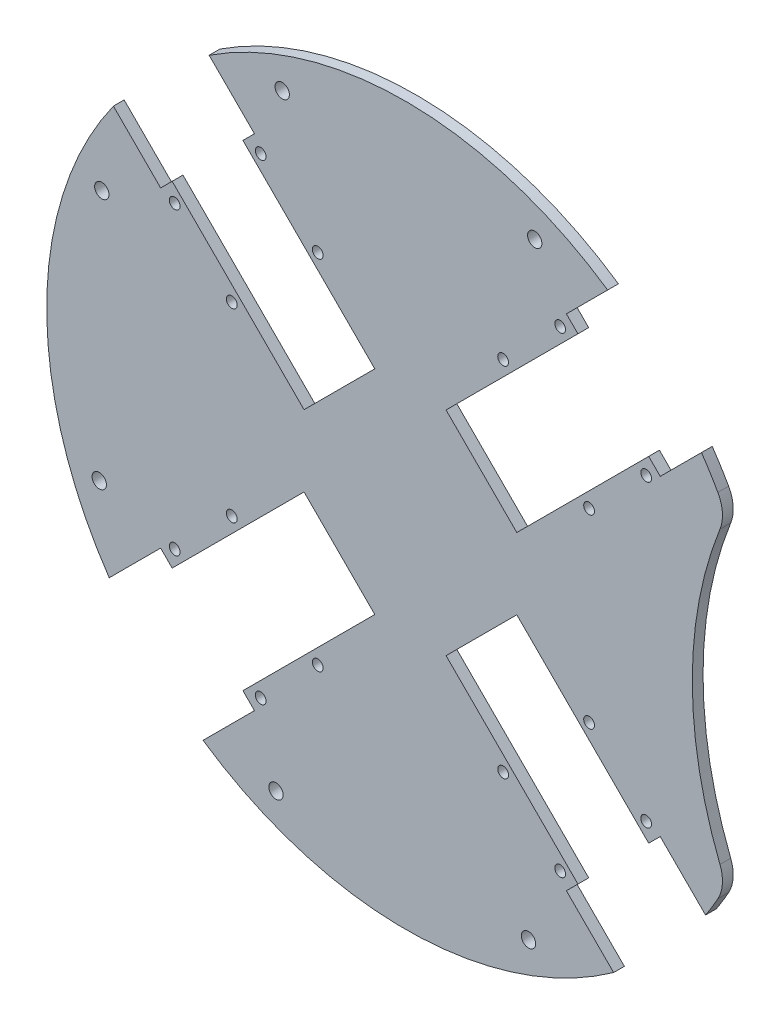
SolidWorks part; units mm, degrees
ref_plane "Alzado" through (0, 0, 0) normal (0, 0, 1) x (1, 0, 0)
ref_plane "Planta" through (0, 0, 0) normal (0, 1, 0) x (1, 0, 0)
ref_plane "Vista lateral" through (0, 0, 0) normal (1, 0, 0) x (0, 0, -1)
sketch "Croquis1" plane through (0, 0, 0) normal (0, 0, 1) x (1, 0, 0)
  circle A0 centre (0, 0) radius 100
  dimension "D1" = 200
extrude "Saliente-Extruir1" add sketch "Croquis1" along normal blind 3
sketch "Croquis3" plane through (0, 0, 3) normal (0, 0, 1) x (1, 0, 0)
  line L0 (0, 0) -> (190, 0) construction
  circle A0 centre (190, 0) radius 110
  dimension "D1" = 220
  dimension "D2" = 190
extrude "Cortar-Extruir1" cut sketch "Croquis3" against normal blind 3
fillet "Redondeo1" radius 10 2 edges at (89.4737, -44.6594, 1.5) (89.4737, 44.6594, 1.5)
sketch "Croquis4" plane through (0, 0, 3) normal (0, 0, 1) x (1, 0, 0)
  line L0 (0, 0) -> (-70.7107, -70.7107) construction
  line L1 (-83.7922, -57.6292) -> (-57.6292, -83.7922)
  line L2 (-57.6292, -83.7922) -> (-42.0729, -68.2358)
  line L3 (-83.7922, -57.6292) -> (-68.2358, -42.0729)
  line L4 (-65.0185, -45.2902) -> (-28.2489, -8.5206)
  line L5 (-68.2358, -42.0729) -> (-65.0185, -45.2902)
  line L6 (-45.2902, -65.0185) -> (-42.0729, -68.2358)
  line L7 (-28.2489, -8.5206) -> (-8.5206, -28.2489)
  line L8 (-8.5206, -28.2489) -> (-45.2902, -65.0185)
  line L9 (0, 0) -> (0, -100) construction
  line L10 (0, 0) -> (-100, 0) construction
  line L11 (-8.5206, 31.0773) -> (-28.2489, 11.3491)
  line L12 (-45.2902, 67.8469) -> (-8.5206, 31.0773)
  line L13 (-28.2489, 11.3491) -> (-65.0185, 48.1186)
  line L14 (-65.0185, 48.1186) -> (-68.2358, 44.9013)
  line L15 (-83.7922, 60.4576) -> (-68.2358, 44.9013)
  line L16 (-57.6292, 86.6206) -> (-83.7922, 60.4576)
  line L17 (-57.6292, 86.6206) -> (-42.0729, 71.0642)
  line L18 (-42.0729, 71.0642) -> (-45.2902, 67.8469)
  line L19 (31.0773, 11.3491) -> (11.3491, 31.0773)
  line L20 (67.8469, 48.1186) -> (31.0773, 11.3491)
  line L21 (11.3491, 31.0773) -> (48.1186, 67.8469)
  line L22 (48.1186, 67.8469) -> (44.9013, 71.0642)
  line L23 (60.4576, 86.6206) -> (44.9013, 71.0642)
  line L24 (86.6206, 60.4576) -> (60.4576, 86.6206)
  line L25 (86.6206, 60.4576) -> (71.0642, 44.9013)
  line L26 (71.0642, 44.9013) -> (67.8469, 48.1186)
  line L27 (11.3491, -28.2489) -> (31.0773, -8.5206)
  line L28 (48.1186, -65.0185) -> (11.3491, -28.2489)
  line L29 (31.0773, -8.5206) -> (67.8469, -45.2902)
  line L30 (67.8469, -45.2902) -> (71.0642, -42.0729)
  line L31 (86.6206, -57.6292) -> (71.0642, -42.0729)
  line L32 (60.4576, -83.7922) -> (86.6206, -57.6292)
  line L33 (60.4576, -83.7922) -> (44.9013, -68.2358)
  line L34 (44.9013, -68.2358) -> (48.1186, -65.0185)
  arc A0 (87.1345, 49.0671) -> (87.1345, -49.0671) centre (0, 0) ccw construction
  point P43 (1.4142, 1.4142)
  dimension "D2" = 22
  dimension "D3" = 22
  dimension "D4" = 27.9
  dimension "D5" = 37
  dimension "D6" = 4.55
  dimension "D7" = 100
  dimension "D8" = 52
  dimension "D9" = 52
  dimension "D10" = 45
  dimension "D11" = 4.55
  dimension "D12" = 4
  dimension "D13" = 13.95
  dimension "D14" = 26
extrude "Cortar-Extruir2" cut sketch "Croquis4" against normal through all
sketch "Croquis5" plane through (0, 0, 3) normal (0, 0, 1) x (1, 0, 0)
  line L0 (-65.0185, -45.2902) -> (-62.19, -42.4618) construction
  line L1 (-28.2489, -8.5206) -> (-65.0185, -45.2902) construction
  line L2 (-62.19, -42.4618) -> (-64.3114, -40.3404) construction
  line L3 (-64.3114, -40.3404) -> (-48.4015, -24.4305) construction
  line L4 (-65.0185, -45.2902) -> (-68.2358, -42.0729) construction
  line L5 (-18.3848, -18.3848) -> (-65.0185, -65.0185) construction
  line L6 (-8.5206, -28.2489) -> (-28.2489, -8.5206) construction
  line L7 (-42.0729, -68.2358) -> (-45.2902, -65.0185) construction
  line L8 (-42.4618, -62.19) -> (-40.3404, -64.3114) construction
  line L9 (-45.2902, -65.0185) -> (-42.4618, -62.19) construction
  line L10 (11.3491, -28.2489) -> (48.1186, -65.0185) construction
  line L11 (-65.0185, 48.1186) -> (-28.2489, 11.3491) construction
  line L12 (-8.5206, 31.0773) -> (-45.2902, 67.8469) construction
  line L13 (48.1186, 67.8469) -> (11.3491, 31.0773) construction
  line L14 (31.0773, 11.3491) -> (67.8469, 48.1186) construction
  line L15 (67.8469, -45.2902) -> (31.0773, -8.5206) construction
  line L16 (-68.2358, 44.9013) -> (-65.0185, 48.1186) construction
  line L17 (-45.2902, 67.8469) -> (-42.0729, 71.0642) construction
  line L18 (44.9013, 71.0642) -> (48.1186, 67.8469) construction
  line L19 (67.8469, 48.1186) -> (71.0642, 44.9013) construction
  line L20 (71.0642, -42.0729) -> (67.8469, -45.2902) construction
  line L21 (48.1186, -65.0185) -> (44.9013, -68.2358) construction
  circle A0 centre (-64.3114, -40.3404) radius 1.5
  circle A1 centre (-48.4015, -24.4305) radius 1.5
  circle A2 centre (-24.4305, -48.4015) radius 1.5
  circle A3 centre (-40.3404, -64.3114) radius 1.5
  circle A4 centre (-24.4305, 51.2299) radius 1.5
  circle A5 centre (-40.3404, 67.1398) radius 1.5
  circle A6 centre (-48.4015, 27.259) radius 1.5
  circle A7 centre (-64.3114, 43.1689) radius 1.5
  circle A8 centre (51.2299, 27.259) radius 1.5
  circle A9 centre (67.1398, 43.1689) radius 1.5
  circle A10 centre (27.259, 51.2299) radius 1.5
  circle A11 centre (43.1689, 67.1398) radius 1.5
  circle A12 centre (27.259, -48.4015) radius 1.5
  circle A13 centre (43.1689, -64.3114) radius 1.5
  circle A14 centre (51.2299, -24.4305) radius 1.5
  circle A15 centre (67.1398, -40.3404) radius 1.5
  point P50 (0, 0)
  dimension "D1" = 3
  dimension "D2" = 3
  dimension "D3" = 3
  dimension "D4" = 3
  dimension "D5" = 4
  dimension "D6" = 26.5
  dimension "D7" = 4
  dimension "D8" = 3
  dimension "D9" = 3
  dimension "D10" = 3
  dimension "D11" = 3
  dimension "D12" = 3
  dimension "D13" = 3
  dimension "D14" = 3
  dimension "D15" = 3
  dimension "D16" = 3
  dimension "D17" = 3
  dimension "D18" = 3
  dimension "D19" = 3
  dimension "D20" = 3
  dimension "D21" = 3
  dimension "D22" = 3
  dimension "D23" = 3
  dimension "D24" = 3
  dimension "D25" = 3
  dimension "D26" = 3
  dimension "D27" = 3
  dimension "D28" = 3
  dimension "D29" = 3
  dimension "D30" = 3
  dimension "D31" = 3
  dimension "D32" = 3
  dimension "D33" = 22.5
  dimension "D34" = 22.5
  dimension "D35" = 22.5
  dimension "D36" = 22.5
  dimension "D37" = 22.5
  dimension "D38" = 22.5
  dimension "D39" = 4
  dimension "D40" = 4
  dimension "D42" = 4
  dimension "D43" = 4
  dimension "D44" = 4
  dimension "D41" = 4
extrude "Cortar-Extruir3" cut sketch "Croquis5" against normal blind 10
sketch "Croquis6" plane through (0, 0, 0) normal (0, 0, -1) x (-1, 0, 0)
  line L0 (-56.4086, 82.5716) -> (-44.9013, 71.0642) construction
  line L2 (-39.2083, 91.993) -> (-36.0717, 84.6335) construction
  arc A0 (54.7132, 83.7046) -> (-56.4086, 82.5716) centre (0, 0) ccw construction
  circle A1 centre (-36.0717, 84.6335) radius 2
  circle A2 centre (34.3384, 85.3515) radius 2
  circle A3 centre (84.6335, 36.0717) radius 2
  circle A4 centre (85.3515, -34.3384) radius 2
  circle A5 centre (36.0717, -84.6335) radius 2
  circle A6 centre (-34.3384, -85.3515) radius 2
  circle A9 centre (-84.6335, -36.0717) radius 2 [skipped]
  circle A10 centre (-85.3515, 34.3384) radius 2 [skipped]
  point P26 (0, 0)
  dimension "D1" = 4
  dimension "D2" = 36.0717
  dimension "D4" = 15.8384
  dimension "D3" = 7.3594
  dimension "D5" = 8
extrude "Cortar-Extruir4" cut sketch "Croquis6" against normal through all
